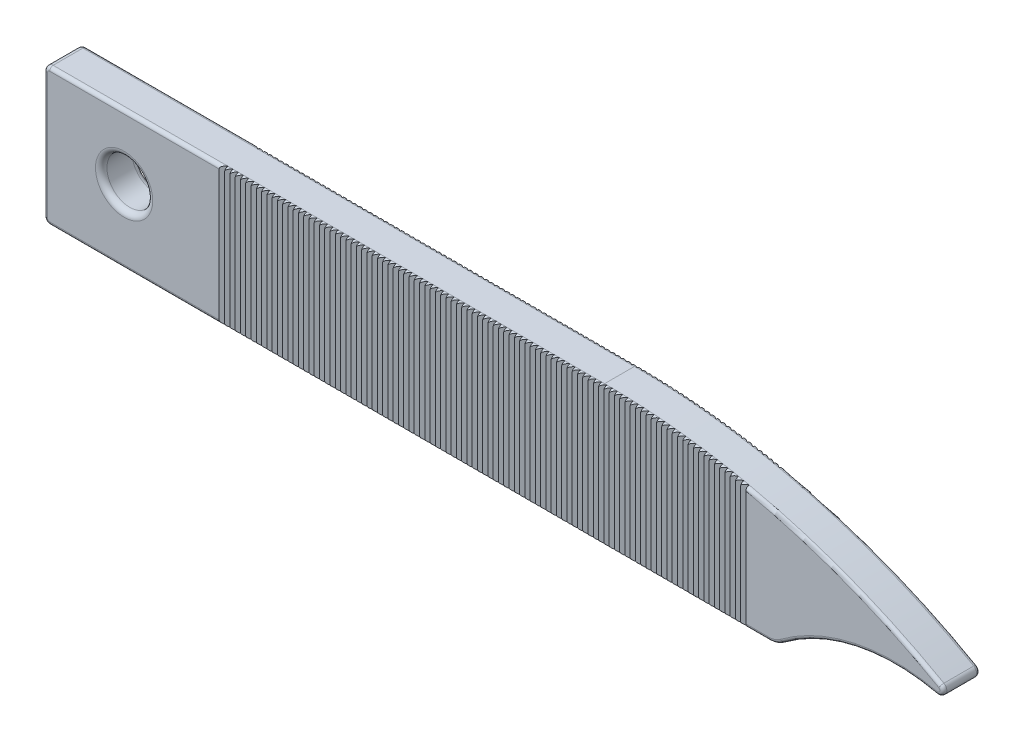
SolidWorks part; units mm, degrees
ref_plane "Front Plane" through (0, 0, 0) normal (0, 0, 1) x (1, 0, 0)
ref_plane "Top Plane" through (0, 0, 0) normal (0, 1, 0) x (1, 0, 0)
ref_plane "Right Plane" through (0, 0, 0) normal (1, 0, 0) x (0, 0, -1)
sketch "Sketch1" plane through (0, 0, 0) normal (0, 0, 1) x (1, 0, 0)
  line L0 (0, 0) -> (0, 6)
  line L1 (0, 6) -> (24.3382, 6)
  line L3 (32, 0) -> (0, 0)
  arc A0 (24.3382, 6) -> (42, 0.25) centre (24.3382, -24) cw
  arc A1 (42, 0.25) -> (32, 0) centre (37.1629, -6.3914) ccw
  dimension "D3" = 30
  dimension "D1" = 6
  dimension "D2" = 42
  dimension "D4" = 32
  dimension "D5" = 5.75
extrude "Boss-Extrude1" add sketch "Sketch1" along normal blind 1.6
fillet "Fillet1" radius 1 1 edges at (32, 0, 0.8)
fillet "Fillet2" radius 0.25 1 edges at (42, 0.25, 0.8)
fillet "Fillet3" radius 0.25 2 edges at (0, 0, 0.8) (0, 6, 0.8)
fillet "Fillet4" radius 0.15 18 edges at (31.9725, 0.0508, 0) (35.4631, 1.647, 0) (39.2714, 1.774, 0) (32.0046, 5.0039, 0) (12.2941, 6, 0) (0.0732, 5.9268, 0) (0, 3, 0) (0.0732, 0.0732, 0) (15.9539, 0, 0) (0.0732, 5.9268, 1.6) (12.2941, 6, 1.6) (32.0046, 5.0039, 1.6) (39.2714, 1.774, 1.6) (35.4631, 1.647, 1.6) (31.9725, 0.0508, 1.6) (15.9539, 0, 1.6) (0.0732, 0.0732, 1.6) (0, 3, 1.6)
sketch "Sketch2" plane through (0, 0, 1.6) normal (0, 0, 1) x (1, 0, 0)
  line L0 (0, 0.25) -> (0, 5.75) construction
  line L1 (31.6579, 0) -> (0.25, 0) construction
  circle A0 centre (3.5, 3.2) radius 1
  point P4 (0, 3)
  dimension "D1" = 2
  dimension "D2" = 3.5
  dimension "D3" = 3.2
extrude "Cut-Extrude1" cut sketch "Sketch2" against normal through all
fillet "Fillet5" radius 0.25 2 edges at (4.5, 3.2, 0) (4.5, 3.2, 1.6)
sketch "Sketch3" plane through (0, 0, 0) normal (0, -1, 0) x (1, 0, 0)
  line L0 (30.4079, 1.6069) -> (30.6579, 1.45)
  line L1 (31.6579, 1.45) -> (0.25, 1.45) construction
  line L2 (30.6579, 1.45) -> (30.6579, 1.6069)
  line L3 (30.6579, 1.6069) -> (30.4079, 1.6069)
  line L4 (31.6579, 1.45) -> (31.6579, 1.6) construction
  line L5 (31.6579, 0.8) -> (29.6181, 0.8) construction
  line L6 (31.6579, 0.15) -> (31.6579, 1.45) construction
  line L7 (30.6579, 0.15) -> (30.6579, -0.0069)
  line L8 (30.4079, -0.0069) -> (30.6579, 0.15)
  line L9 (30.6579, -0.0069) -> (30.4079, -0.0069)
  dimension "D1" = 0.25
  dimension "D2" = 1
extrude "Cut-Extrude2" cut sketch "Sketch3" against normal blind 14.6
pattern_linear "LPattern1" count 100 spacing 0.23 along (-1, 0, 0) of "Cut-Extrude2"
